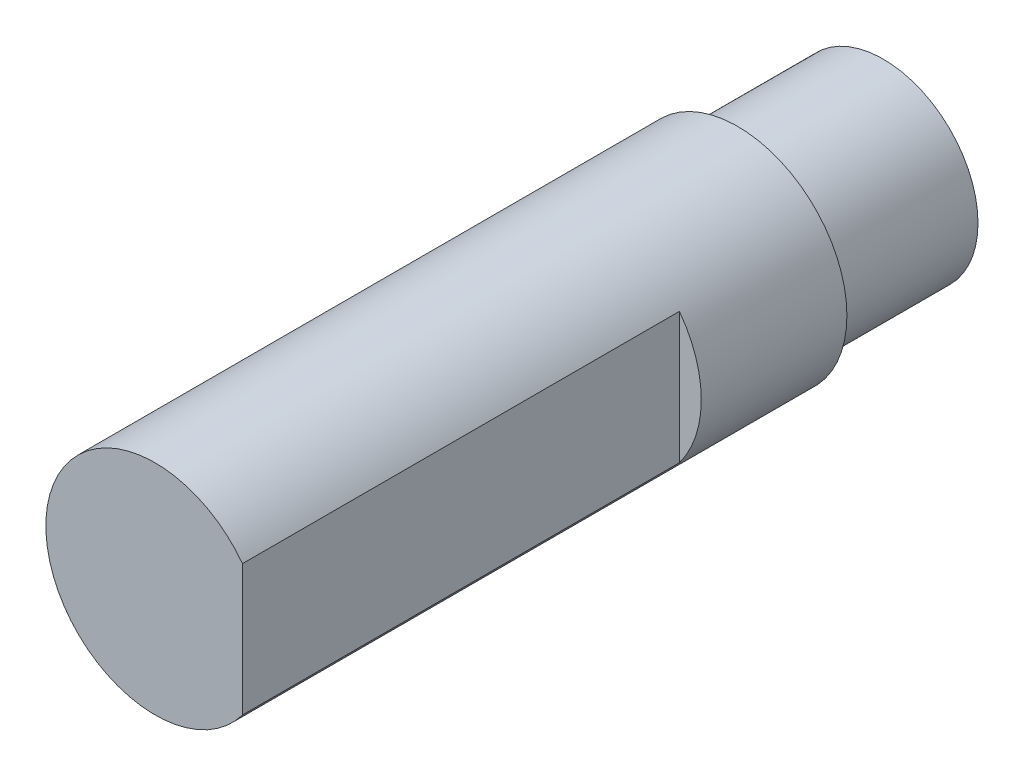
SolidWorks part; units mm, degrees
ref_plane "Front Plane" through (0, 0, 0) normal (0, 0, 1) x (1, 0, 0)
ref_plane "Top Plane" through (0, 0, 0) normal (0, 1, 0) x (1, 0, 0)
ref_plane "Right Plane" through (0, 0, 0) normal (1, 0, 0) x (0, 0, -1)
sketch "S01 - Output shaft" plane through (0, 0, 0) normal (0, 0, 1) x (1, 0, 0)
  circle A0 centre (0, 0) radius 3
  dimension "D1" = 6
extrude "01 - Output shaft" add sketch "S01 - Output shaft" along normal blind 16 from offset 6
sketch "S02 - D flat on exposed tip" plane through (0, 0, 0) normal (0, 0, 1) x (1, 0, 0)
  line L0 (2.4, -4) -> (4, -4)
  line L1 (4, -4) -> (4, 4)
  line L2 (4, 4) -> (2.4, 4)
  line L3 (2.4, 4) -> (2.4, -4)
  dimension "D1" = 2.4
  dimension "D2" = 4
  dimension "D3" = 4
  dimension "D4" = 4
extrude "02 - D flat on exposed tip" cut sketch "S02 - D flat on exposed tip" along normal blind 12.2 from offset 10
sketch "S03 - Output pilot in gearbox nose" plane through (0, 0, 0) normal (0, 0, 1) x (1, 0, 0)
  circle A0 centre (0, 0) radius 2.6
  dimension "D1" = 5.2
extrude "03 - Output pilot in gearbox nose" add sketch "S03 - Output pilot in gearbox nose" along normal blind 4 from offset 2
